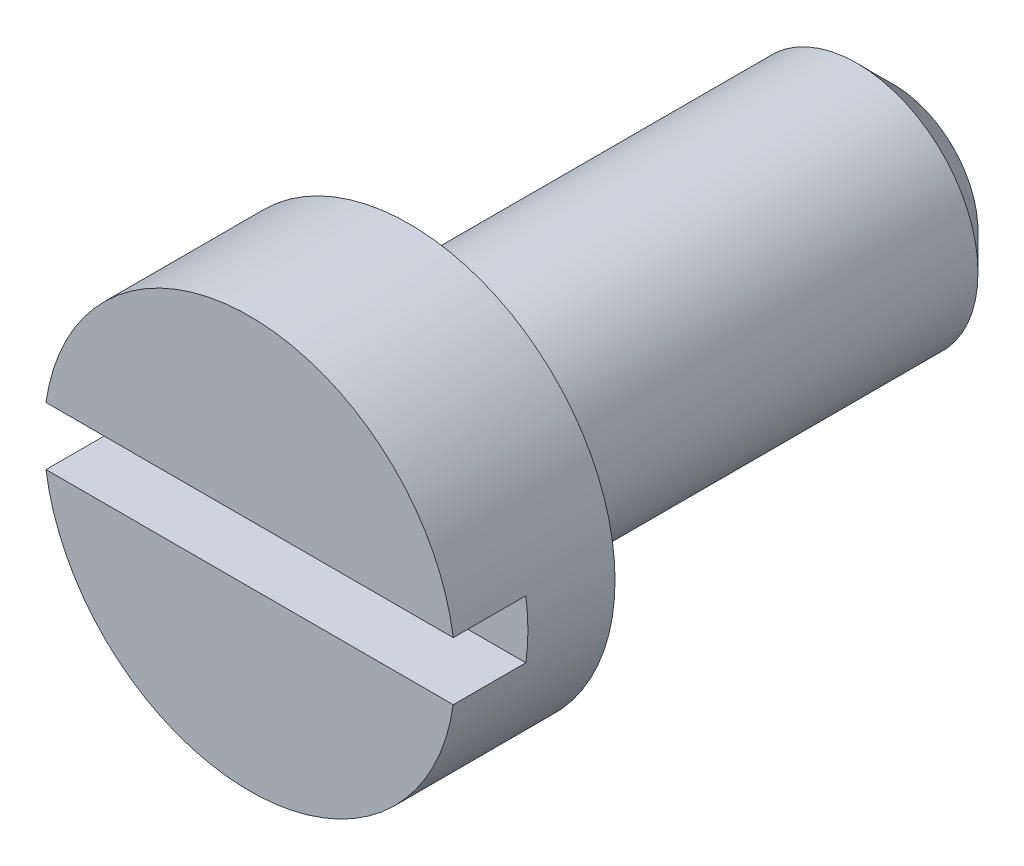
SolidWorks part; units mm, degrees
ref_plane "Спереди" through (0, 0, 0) normal (0, 0, 1) x (1, 0, 0)
ref_plane "Сверху" through (0, 0, 0) normal (0, 1, 0) x (1, 0, 0)
ref_plane "Справа" through (0, 0, 0) normal (1, 0, 0) x (0, 0, -1)
sketch "Эскиз12" plane through (0, 0, 0) normal (0, 0, 1) x (1, 0, 0)
  circle A0 centre (0, 0) radius 4.25
extrude "Вытянуть3" add sketch "Эскиз12" along normal blind 3.3
sketch "Эскиз13" plane through (0, 0, 0) normal (0, 0, -1) x (-1, 0, 0)
  circle A0 centre (0, 0) radius 2.5
extrude "Вытянуть4" add sketch "Эскиз13" along normal blind 10
sketch "Эскиз14" plane through (0, 0, 3.3) normal (0, 0, 1) x (1, 0, 0)
  line L0 (-4.25, 0) -> (4.25, 0) construction
  circle A0 centre (0, 0) radius 4.25 construction
sketch "Эскиз20" plane through (0, 0, 3.3) normal (0, 0, 1) x (1, 0, 0)
  line L0 (-4.25, 0) -> (4.25, 0) construction
  line L1 (-4.5688, 0.6) -> (4.4378, 0.6)
  line L2 (-4.5688, 0.6) -> (-4.5688, -0.6)
  line L3 (-4.5688, -0.6) -> (4.4378, -0.6)
  line L4 (4.4378, 0.6) -> (4.4378, -0.6)
  dimension "D1" = 0.6
  dimension "D2" = 0.6
extrude "Вырез-Вытянуть8" cut sketch "Эскиз20" against normal blind 1.5
chamfer "Фаска1" distance 0.75 angle 45 1 edges at (-2.5, 0, -10)
